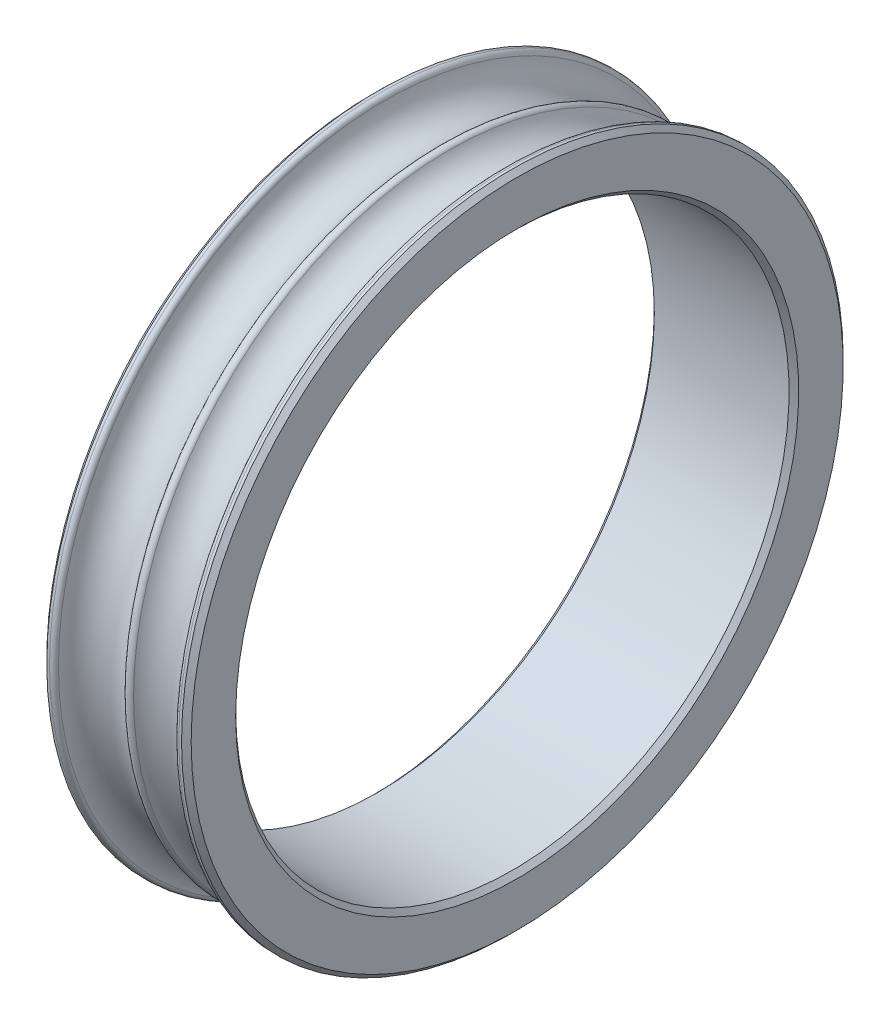
SolidWorks part; units mm, degrees
ref_plane "前视基准面" through (0, 0, 0) normal (0, 0, 1) x (1, 0, 0)
ref_plane "上视基准面" through (0, 0, 0) normal (0, 1, 0) x (1, 0, 0)
ref_plane "右视基准面" through (0, 0, 0) normal (1, 0, 0) x (0, 0, -1)
sketch "草图1" plane through (0, 0, 0) normal (0, 0, 1) x (1, 0, 0)
  line L0 (-16.5806, 0) -> (15.9821, 0) construction
  line L1 (0, 30.6673) -> (0, -24.0928) construction
  line L3 (6, 23) -> (0, 23)
  line L6 (5, 27.5) -> (6, 27.5)
  line L7 (6, 27.5) -> (6, 23)
  line L8 (-6, 23) -> (0, 23)
  line L9 (-6, 27.5) -> (-6, 23)
  line L10 (-5, 27.5) -> (-6, 27.5)
  arc A0 (0, 27.5) -> (5, 27.5) centre (2.5, 27.5) ccw
  arc A2 (0, 27.5) -> (-5, 27.5) centre (-2.5, 27.5) cw
  point P3 (0, 0)
  point P9 (5, 23)
  point P10 (3, 23)
  point P12 (5, 23)
  point P14 (5, 23)
  point P15 (-3, 23)
  point P17 (5, 23)
  point P18 (5.1885, 23)
  point P19 (0, 0)
  dimension "D1" = 2.5
  dimension "D2" = 23
  dimension "D3" = 27.5
  dimension "D4" = 12
revolve "旋转1" add sketch "草图1" angle 360 about L0
fillet "圆角1" radius 0.4 3 edges at (-5, 0, 27.5) (5, 0, 27.5) (0, 0, 27.5)
chamfer "倒角1" distance 0.4 angle 45 4 edges at (6, 0, 23) (6, 0, 27.5) (-6, 0, 27.5) (-6, 0, 23)
